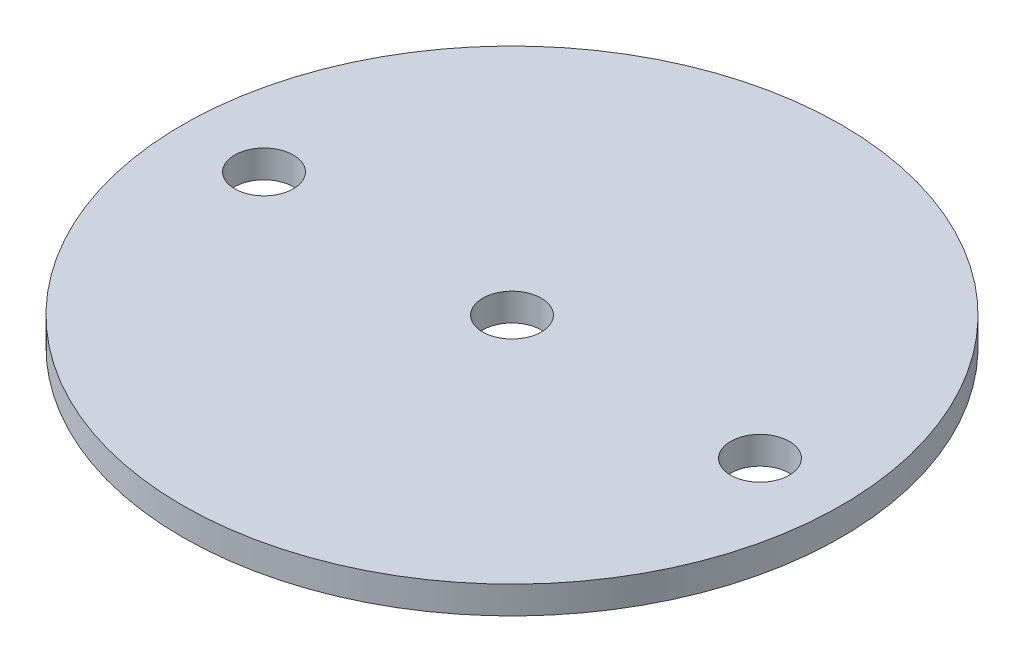
SolidWorks part; units mm, degrees
ref_plane "Front Plane" through (0, 0, 0) normal (0, 0, 1) x (1, 0, 0)
ref_plane "Top Plane" through (0, 0, 0) normal (0, 1, 0) x (1, 0, 0)
ref_plane "Right Plane" through (0, 0, 0) normal (1, 0, 0) x (0, 0, -1)
sketch "Sketch1" plane through (0, 0, 0) normal (0, 1, 0) x (1, 0, 0)
  circle A0 centre (0, 0) radius 37.973
  dimension "D1" = 75.946
extrude "Boss-Extrude1" add sketch "Sketch1" along normal mid plane 3.175
hole_wizard "H (0.266) Diameter Hole1" positions "Sketch2" profile "Sketch3" hole size "H" standard "ANSI Inch" end condition through all
sketch "Sketch2" plane through (0, 1.5875, 0) normal (0, 1, 0) x (1, 0, 0)
  line L0 (-28.575, 0) -> (28.575, 0) construction
  point P0 (-28.575, 0)
  point P2 (28.575, 0)
  dimension "D1" = 57.15
sketch "Sketch3" plane through (-28.575, 1.5875, 0) normal (1, 0, 0) x (0, 0, 1)
  line L0 (0, 0) -> (0, 3.175)
  line L1 (0, 3.175) -> (3.3782, 3.175)
  line L2 (3.3782, 3.175) -> (3.3782, 0)
  line L5 (3.3782, 0) -> (0, 0)
  line L11 (0, -6.35) -> (0, 107.95) construction
  dimension "Thru Hole Dia." = 6.7564
  dimension "Thru Hole Depth" = 3.175
hole_wizard "H (0.266) Diameter Hole2" positions "Sketch11" profile "Sketch12" hole size "H" standard "ANSI Inch" end condition through all
sketch "Sketch11" plane through (0, 1.5875, 0) normal (0, 1, 0) x (1, 0, 0)
  point P0 (0, 0)
sketch "Sketch12" plane through (0, 1.5875, 0) normal (1, 0, 0) x (0, 0, 1)
  line L0 (0, 0) -> (0, 3.175)
  line L1 (0, 3.175) -> (3.3782, 3.175)
  line L2 (3.3782, 3.175) -> (3.3782, 0)
  line L5 (3.3782, 0) -> (0, 0)
  line L11 (0, -6.35) -> (0, 107.95) construction
  dimension "Thru Hole Dia." = 6.7564
  dimension "Thru Hole Depth" = 3.175
equation "\"airframeInnerDiameter\"=3"
equation "\"airframeBulkheadThickness\"=0.125"
equation "\"D1@Boss-Extrude1\"=\"airframeBulkheadThickness\""
equation "\"recoveryBayInnerDiameter\"=2.88"
equation "\"D1@Sketch1\"    = \"airframeInnerDiameter\"-0.01"
equation "\"threaded rod distance\"= 2.25"
equation "\"D1@Sketch2\"=\"threaded rod distance\""
